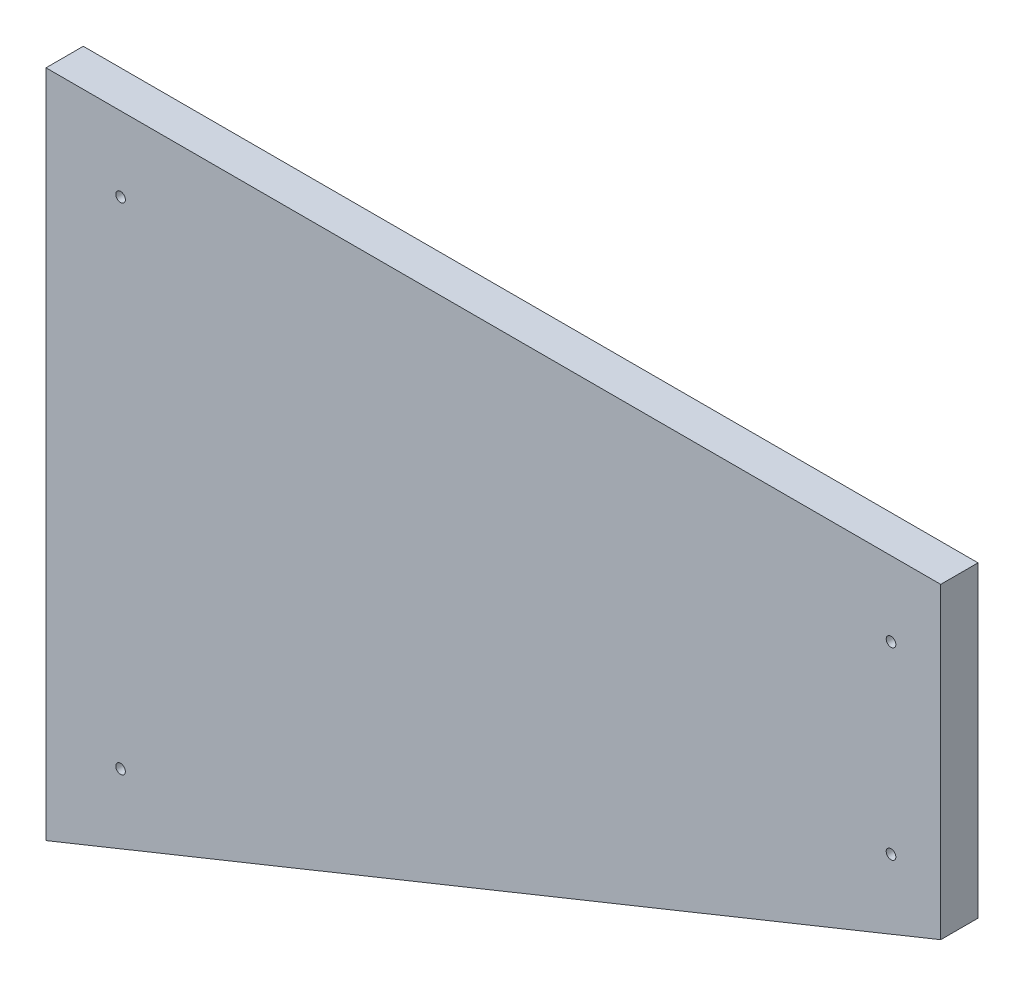
SolidWorks part; units mm, degrees
material "Beech"
ref_plane "Front Plane" through (0, 0, 0) normal (0, 0, 1) x (1, 0, 0)
ref_plane "Top Plane" through (0, 0, 0) normal (0, 1, 0) x (1, 0, 0)
ref_plane "Right Plane" through (0, 0, 0) normal (1, 0, 0) x (0, 0, -1)
sketch "Sketch1" plane through (0, 0, 0) normal (0, 0, 1) x (1, 0, 0)
  line L0 (2683.51, 6641.7419) -> (3140.71, 6826.4627) construction
  line L1 (2683.51, 7002.78) -> (2683.51, 5935.98) construction
  line L8 (2683.51, 6983.73) -> (2683.51, 6641.7419)
  line L9 (2683.51, 6641.7419) -> (3140.71, 6826.4627)
  line L10 (3140.71, 6826.4627) -> (3140.71, 6983.73)
  line L11 (3140.71, 6983.73) -> (2683.51, 6983.73)
extrude "Boss-Extrude1" add sketch "Sketch1" along normal blind 19.05
hole_wizard "CSK for #8 Flat Head Machine Screw (100)1" positions "Sketch2" profile "Sketch3" countersink size "#8" standard "ANSI Inch" end condition through all
sketch "Sketch2" plane through (0, 0, 0) normal (0, 0, -1) x (0, 1, 0)
  point P0 (6692.5419, 2721.61)
  point P1 (6945.63, 2721.61)
  point P2 (6945.63, 3115.31)
  point P3 (6851.607, 3115.31)
sketch "Sketch3" plane through (2721.61, 6692.5419, 0) normal (1, 0, 0) x (0, 1, 0)
  line L0 (0, 0) -> (0, 19.05)
  line L1 (0, 19.05) -> (2.4574, 19.05)
  line L2 (2.4574, 19.05) -> (2.4574, 1.4759)
  line L3 (2.4574, 1.4759) -> (4.2164, 0)
  line L4 (4.2164, 0) -> (0, 0)
  line L5 (-2.4574, 1.4759) -> (-4.2164, 0) construction
  line L6 (0, -6.35) -> (0, 107.95) construction
  dimension "Thru Hole Dia." = 4.9149
  dimension "Thru Hole Depth" = 19.05
  dimension "Near C'Sink Dia." = 8.4328
  dimension "Near C'Sink Angle" = 100
